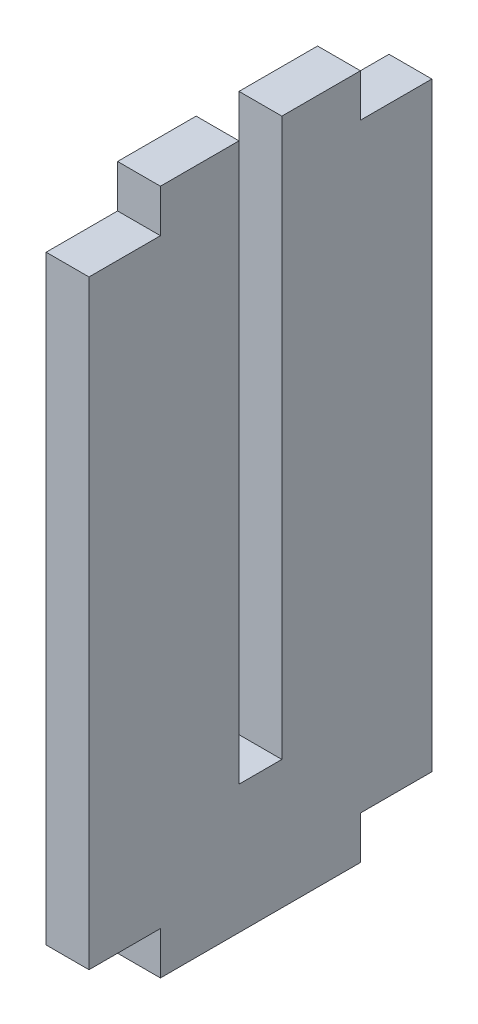
SolidWorks part; units mm, degrees
ref_plane "Front Plane" through (0, 0, 0) normal (0, 0, 1) x (1, 0, 0)
ref_plane "Top Plane" through (0, 0, 0) normal (0, 1, 0) x (1, 0, 0)
ref_plane "Right Plane" through (0, 0, 0) normal (1, 0, 0) x (0, 0, -1)
sketch "Sketch1" plane through (0, 0, 0) normal (1, 0, 0) x (0, 0, -1)
  line L1 (0, 0) -> (50.8, 0)
  line L2 (0, 0) -> (0, 101.6)
  line L3 (0, 101.6) -> (50.8, 101.6)
  line L4 (50.8, 0) -> (50.8, 101.6)
  line L5 (25.4, 101.6) -> (25.4, 0) construction
  line L6 (0, 50.8) -> (50.8, 50.8) construction
  point P112 (25.4, 50.8)
  dimension "D1" = 101.6
  dimension "D2" = 50.8
extrude "Boss-Extrude1" add sketch "Sketch1" along normal blind 6.35
sketch "Sketch2" plane through (6.35, 0, 0) normal (1, 0, 0) x (0, 0, -1)
  line L0 (25.4, 101.6) -> (25.4, 0) construction
  line L1 (50.8, 101.6) -> (0, 101.6) construction
  line L2 (0, 0) -> (50.8, 0) construction
  line L3 (0, 19.05) -> (50.8, 19.05) construction
  line L4 (0, 101.6) -> (0, 0) construction
  line L5 (50.8, 0) -> (50.8, 101.6) construction
  line L6 (40.2167, 101.6) -> (40.2167, 95.25)
  line L7 (22.225, 101.6) -> (28.575, 101.6)
  line L8 (22.225, 101.6) -> (22.225, 19.05)
  line L9 (22.225, 19.05) -> (28.575, 19.05)
  line L10 (28.575, 101.6) -> (28.575, 19.05)
  line L11 (25.4, 19.05) -> (25.4, 101.6) construction
  line L12 (22.225, 60.325) -> (28.575, 60.325) construction
  line L13 (0, 101.6) -> (10.5833, 101.6)
  line L14 (0, 101.6) -> (0, 95.25)
  line L15 (0, 95.25) -> (10.5833, 95.25)
  line L16 (10.5833, 101.6) -> (10.5833, 95.25)
  line L17 (5.2917, 95.25) -> (5.2917, 101.6) construction
  line L18 (0, 98.425) -> (10.5833, 98.425) construction
  line L19 (50.8, 95.25) -> (40.2167, 95.25)
  line L20 (50.8, 101.6) -> (50.8, 95.25)
  line L21 (50.8, 101.6) -> (40.2167, 101.6)
  line L22 (0, 50.8) -> (50.8, 50.8) construction
  line L23 (50.8, 0) -> (40.2167, 0)
  line L24 (50.8, 0) -> (50.8, 6.35)
  line L25 (50.8, 6.35) -> (40.2167, 6.35)
  line L26 (40.2167, 0) -> (40.2167, 6.35)
  line L27 (0, 3.175) -> (10.5833, 3.175) construction
  line L28 (5.2917, 6.35) -> (5.2917, 0) construction
  line L29 (10.5833, 0) -> (10.5833, 6.35)
  line L30 (0, 6.35) -> (10.5833, 6.35)
  line L31 (0, 0) -> (0, 6.35)
  line L32 (0, 0) -> (10.5833, 0)
  point P38 (5.2917, 3.175)
  point P160 (5.2917, 98.425)
  point P380 (25.4, 60.325)
  dimension "D1" = 19.05
  dimension "D2" = 6.35
  dimension "D3" = 6.35
  dimension "D4" = 10.5833
extrude "Cut-Extrude1" cut sketch "Sketch2" against normal blind 6.35
equation "\"Stock Thickness\"= .25in"
equation "\"D1@Boss-Extrude1\"=\"Stock Thickness\""
equation "\"Joint Length\"= .75in"
equation "\"D1@Sketch2\"=\"Joint Length\""
equation "\"D2@Sketch2\"=\"Stock Thickness\""
equation "\"D1@Cut-Extrude1\"=\"Stock Thickness\""
equation "\"D3@Sketch2\"=\"Stock Thickness\""
equation "\"D4@Sketch2\"=\"D2@Sketch1\"/3 - \"Stock Thickness\""
